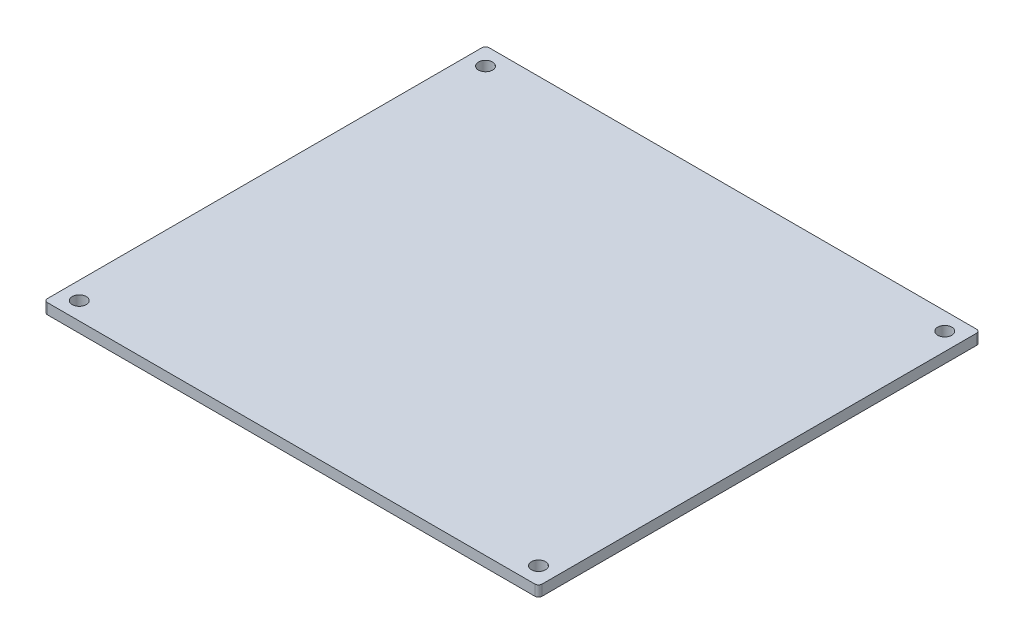
SolidWorks part; units mm, degrees
ref_plane "Front (XY)" through (0, 0, 0) normal (0, 0, 1) x (1, 0, 0)
ref_plane "Top (XZ)" through (0, 0, 0) normal (0, 1, 0) x (1, 0, 0)
ref_plane "Right (YZ)" through (0, 0, 0) normal (1, 0, 0) x (0, 0, -1)
sketch "Sketch1" plane through (0, 0, 0) normal (0, 1, 0) x (1, 0, 0)
  line L0 (-140, 125) -> (-140, -125)
  line L1 (-140, -125) -> (140, -125)
  line L2 (140, -125) -> (140, 125)
  line L3 (140, 125) -> (-140, 125)
  point P4 (0, 125)
  point P5 (140, 0)
  dimension "D1" = 280
  dimension "D2" = 250
extrude "Boss-Extrude1" add sketch "Sketch1" along normal blind 6
fillet "Fillet1" radius 2 4 edges at (-140, 3, -125) (-140, 3, 125) (140, 3, -125) (140, 3, 125)
sketch "Sketch2" plane through (0, 6, 0) normal (0, 1, 0) x (1, 0, 0)
  line L0 (138, 125) -> (-138, 125) construction
  line L1 (-140, 123) -> (-140, -123) construction
  line L2 (140, -123) -> (140, 123) construction
  line L3 (-138, -125) -> (138, -125) construction
  circle A0 centre (-130, 115) radius 4
  circle A1 centre (130, 115) radius 4
  circle A2 centre (130, -115) radius 4
  circle A3 centre (-130, -115) radius 4
  point P12 (0, 0)
  dimension "D1" = 8
  dimension "D2" = 10
  dimension "D3" = 10
  dimension "D4" = 10
  dimension "D5" = 10
extrude "Cut-Extrude1" cut sketch "Sketch2" against normal through all
